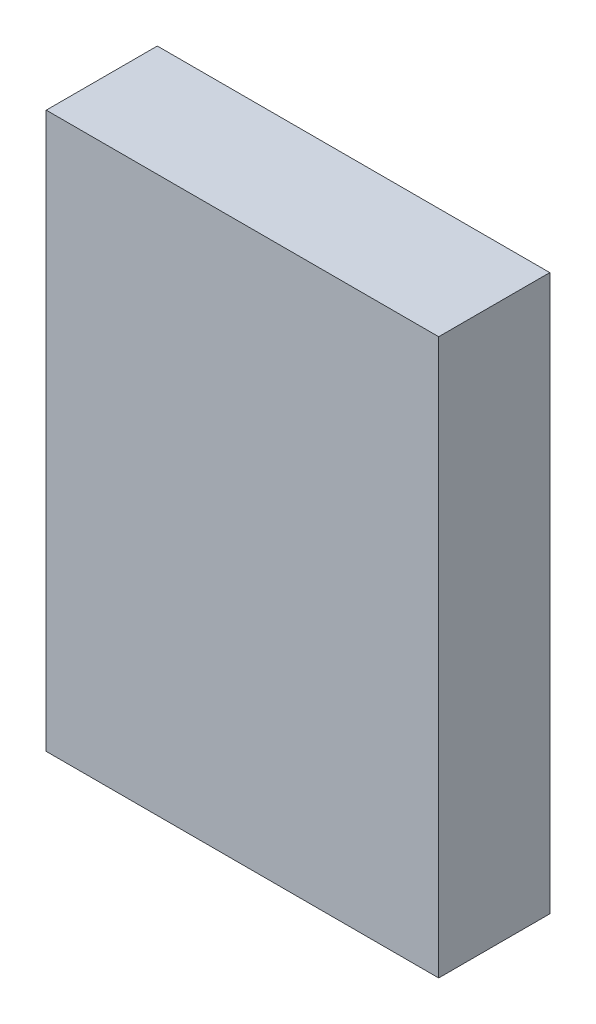
SolidWorks part; units mm, degrees
ref_plane "Plan de face" through (0, 0, 0) normal (0, 0, 1) x (1, 0, 0)
ref_plane "Plan de dessus" through (0, 0, 0) normal (0, 1, 0) x (1, 0, 0)
ref_plane "Plan de droite" through (0, 0, 0) normal (1, 0, 0) x (0, 0, -1)
sketch "Esquisse1" plane through (0, 0, 0) normal (0, 0, 1) x (1, 0, 0)
  line L1 (0, 0) -> (53, 0)
  line L2 (0, 0) -> (0, 75)
  line L3 (0, 75) -> (53, 75)
  line L4 (53, 0) -> (53, 75)
  dimension "D1" = 53
  dimension "D2" = 75
extrude "Boss.-Extru.1" add sketch "Esquisse1" along normal blind 15
